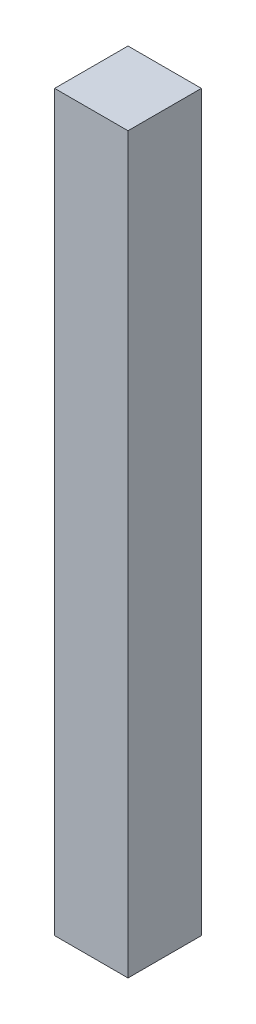
SolidWorks part; units mm, degrees
ref_plane "Спереди" through (0, 0, 0) normal (0, 0, 1) x (1, 0, 0)
ref_plane "Сверху" through (0, 0, 0) normal (0, 1, 0) x (1, 0, 0)
ref_plane "Справа" through (0, 0, 0) normal (1, 0, 0) x (0, 0, -1)
other "Configuration Table"
sketch "Эскиз1" plane through (0, 0, 0) normal (0, 1, 0) x (1, 0, 0)
  line L1 (-10, -10) -> (10, -10)
  line L2 (-10, -10) -> (-10, 10)
  line L3 (-10, 10) -> (10, 10)
  line L4 (10, -10) -> (10, 10)
  line L5 (-10, -10) -> (10, 10) construction
  line L6 (-10, 10) -> (10, -10) construction
  point P0 (0, 0)
  dimension "D1" = 20
extrude "Бобышка-Вытянуть1" add sketch "Эскиз1" along normal blind 200
equation "\"DownLong\" = 200мм"
